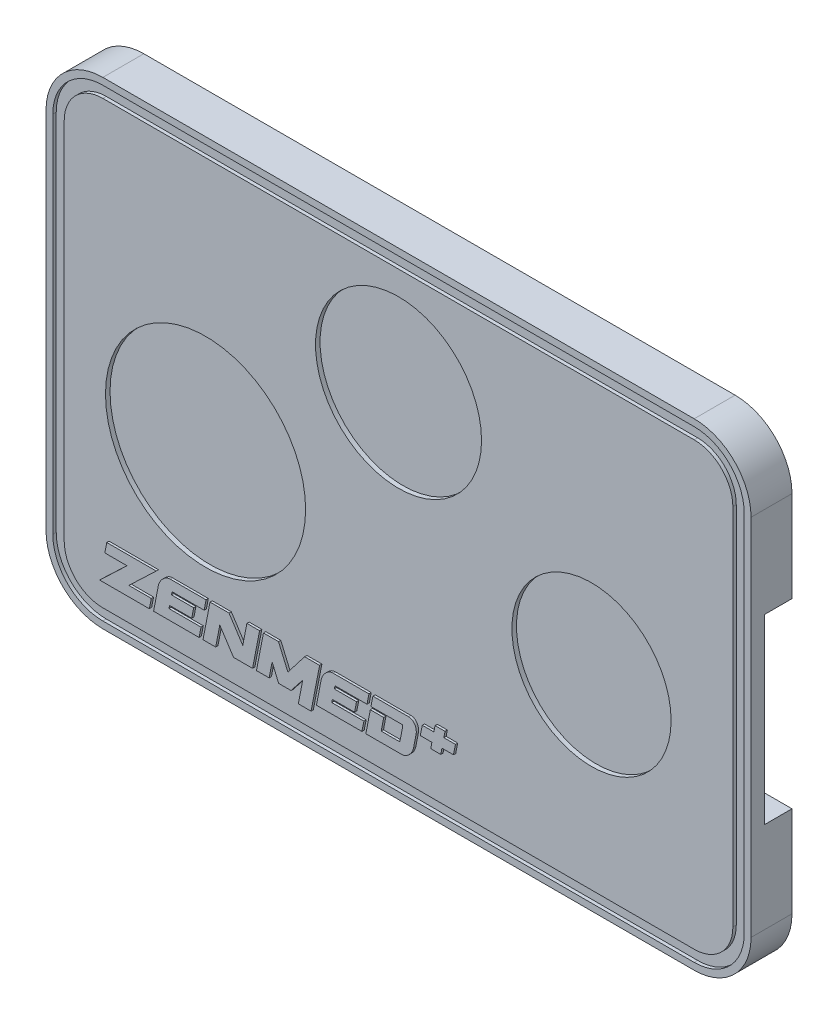
SolidWorks part; units mm, degrees
ref_plane "Front Plane" through (0, 0, 0) normal (0, 0, 1) x (1, 0, 0)
ref_plane "Top Plane" through (0, 0, 0) normal (0, 1, 0) x (1, 0, 0)
ref_plane "Right Plane" through (0, 0, 0) normal (1, 0, 0) x (0, 0, -1)
sketch "Sketch2" plane through (0, 0, 0) normal (0, 0, 1) x (1, 0, 0)
  line L1 (-130, 105) -> (130, 105)
  line L2 (-155, 80) -> (-155, -80)
  line L3 (-130, -105) -> (130, -105)
  line L4 (155, 80) -> (155, -80)
  arc A0 (130, 105) -> (155, 80) centre (130, 80) cw
  arc A1 (130, -105) -> (155, -80) centre (130, -80) ccw
  arc A2 (-155, -80) -> (-130, -105) centre (-130, -80) ccw
  arc A3 (-130, 105) -> (-155, 80) centre (-130, 80) ccw
  point P7 (155, 105)
  point P10 (155, -105)
  point P15 (-155, 105)
  dimension "D5" = 25
  dimension "D1" = 310
  dimension "D2" = 210
  dimension "D3" = 105
  dimension "D4" = 155
extrude "Boss-Extrude1" add sketch "Sketch2" along normal blind 1.5
sketch "Sketch5" plane through (0, 0, 1.5) normal (0, 0, 1) x (1, 0, 0)
  text T0 "ZENMED" font "Gemina Semi-Italic" height in points 60
extrude "Boss-Extrude4" add sketch "Sketch5" along normal blind 1
sketch "Sketch6" plane through (0, 0, 1.5) normal (0, 0, 1) x (1, 0, 0)
  text T0 "+" font "Gemina Semi-Italic" height in points 60
extrude "Boss-Extrude5" add sketch "Sketch6" along normal blind 1
sketch "Sketch8" plane through (0, 0, 0) normal (0, 0, -1) x (-1, 0, 0)
  line L4 (-155, 80) -> (-155, -80)
  line L5 (-130, -105) -> (130, -105)
  line L6 (155, -80) -> (155, 80)
  line L7 (130, 105) -> (-130, 105)
  line L8 (-155, 80) -> (-155, -80)
  line L9 (-130, -105) -> (130, -105)
  line L10 (155, -80) -> (155, 80)
  line L11 (130, 105) -> (-130, 105)
  arc A4 (-130, 105) -> (-155, 80) centre (-130, 80) ccw
  arc A5 (-155, -80) -> (-130, -105) centre (-130, -80) ccw
  arc A6 (130, -105) -> (155, -80) centre (130, -80) ccw
  arc A7 (155, 80) -> (130, 105) centre (130, 80) ccw
  arc A8 (-130, 105) -> (-155, 80) centre (-130, 80) ccw
  arc A9 (-155, -80) -> (-130, -105) centre (-130, -80) ccw
  arc A10 (130, -105) -> (155, -80) centre (130, -80) ccw
  arc A11 (155, 80) -> (130, 105) centre (130, 80) ccw
  dimension "D1" = 0
extrude "Boss-Extrude6" add sketch "Sketch8" along normal blind 10.5
sketch "Sketch10" plane through (0, 0, 1.5) normal (0, 0, 1) x (1, 0, 0)
  line L0 (130, 105) -> (-130, 105) construction
  line L3 (0, -20) -> (0, 50) construction
  circle A0 centre (-84.8528, -15) radius 44
  circle A1 centre (84.8528, -15) radius 35
  circle A2 centre (0, 50) radius 36.5
  point P2 (0, 105)
  point P3 (0, 0)
  point P4 (120.2156, -47.1455)
  point P5 (0, 0)
  point P9 (0, 0)
  point P10 (0, 0)
  dimension "D4" = 70
  dimension "D5" = 88
  dimension "D1" = 73
  dimension "D2" = 55
extrude "Cut-Extrude3" cut sketch "Sketch10" against normal blind 2
sketch "Sketch11" plane through (0, 0, 1.5) normal (0, 0, 1) x (1, 0, 0)
  line L4 (130, 102) -> (-130, 102)
  line L5 (-152, 80) -> (-152, -80)
  line L6 (-130, -102) -> (130, -102)
  line L7 (152, -80) -> (152, 80)
  line L8 (130, 97) -> (-130, 97)
  line L9 (-147, 80) -> (-147, -80)
  line L10 (-130, -97) -> (130, -97)
  line L11 (147, -80) -> (147, 80)
  line L12 (130, 97) -> (-130, 97)
  line L13 (-147, 80) -> (-147, -80)
  line L14 (-130, -97) -> (130, -97)
  line L15 (147, -80) -> (147, 80)
  arc A4 (-130, 102) -> (-152, 80) centre (-130, 80) ccw
  arc A5 (-152, -80) -> (-130, -102) centre (-130, -80) ccw
  arc A6 (130, -102) -> (152, -80) centre (130, -80) ccw
  arc A7 (152, 80) -> (130, 102) centre (130, 80) ccw
  arc A8 (147, 80) -> (130, 97) centre (130, 80) ccw
  arc A9 (-130, 97) -> (-147, 80) centre (-130, 80) ccw
  arc A10 (-147, -80) -> (-130, -97) centre (-130, -80) ccw
  arc A11 (130, -97) -> (147, -80) centre (130, -80) ccw
  arc A12 (147, 80) -> (130, 97) centre (130, 80) ccw
  arc A13 (-130, 97) -> (-147, 80) centre (-130, 80) ccw
  arc A14 (-147, -80) -> (-130, -97) centre (-130, -80) ccw
  arc A15 (130, -97) -> (147, -80) centre (130, -80) ccw
  dimension "D1" = 8
  dimension "D2" = 5
extrude "Cut-Extrude4" cut sketch "Sketch11" against normal blind 1.5
sketch "Sketch15" plane through (0, 0, -10.5) normal (0, 0, -1) x (-1, 0, 0)
  line L4 (-155, 80) -> (-155, -80)
  line L5 (-130, -105) -> (130, -105)
  line L6 (155, -80) -> (155, 80)
  line L7 (130, 105) -> (-130, 105)
  line L8 (-155, 80) -> (-155, -80)
  line L9 (-130, -105) -> (130, -105)
  line L10 (155, -80) -> (155, 80)
  line L11 (130, 105) -> (-130, 105)
  arc A4 (-130, 105) -> (-155, 80) centre (-130, 80) ccw
  arc A5 (-155, -80) -> (-130, -105) centre (-130, -80) ccw
  arc A6 (130, -105) -> (155, -80) centre (130, -80) ccw
  arc A7 (155, 80) -> (130, 105) centre (130, 80) ccw
  arc A8 (-130, 105) -> (-155, 80) centre (-130, 80) ccw
  arc A9 (-155, -80) -> (-130, -105) centre (-130, -80) ccw
  arc A10 (130, -105) -> (155, -80) centre (130, -80) ccw
  arc A11 (155, 80) -> (130, 105) centre (130, 80) ccw
  dimension "D1" = 0
extrude "Boss-Extrude8" add sketch "Sketch15" along normal blind 6
sketch "Sketch12" plane through (0, -105, 0) normal (0, -1, 0) x (1, 0, 0)
  line L1 (-155, 1.5) -> (155, 1.5) construction
  text T0 "ZENITH ALLMART EXperience" font "Century Gothic" height in points 24
extrude "Cut-Extrude5" cut sketch "Sketch12" against normal blind 0.5
sketch "Sketch16" plane through (0, 0, -16.5) normal (0, 0, -1) x (-1, 0, 0)
  line L0 (155, 0) -> (-155, 0) construction
  line L1 (155, -80) -> (155, 80) construction
  line L2 (-155, 80) -> (-155, -80) construction
  line L4 (155, -40) -> (105, -40)
  line L5 (155, -40) -> (155, 40)
  line L6 (155, 40) -> (105, 40)
  line L7 (105, -40) -> (105, 40)
  line L8 (-155, -40) -> (-105, -40)
  line L9 (-155, -40) -> (-155, 40)
  line L10 (-155, 40) -> (-105, 40)
  line L11 (-105, -40) -> (-105, 40)
  dimension "D1" = 50
  dimension "D2" = 80
  dimension "D3" = 40
  dimension "D4" = 80
  dimension "D5" = 50
  dimension "D6" = 40
extrude "Cut-Extrude7" cut sketch "Sketch16" against normal blind 12
fillet "Fillet2" radius 10 4 edges at (105, 40, -10.5) (105, -40, -10.5) (-105, 40, -10.5) (-105, -40, -10.5)
